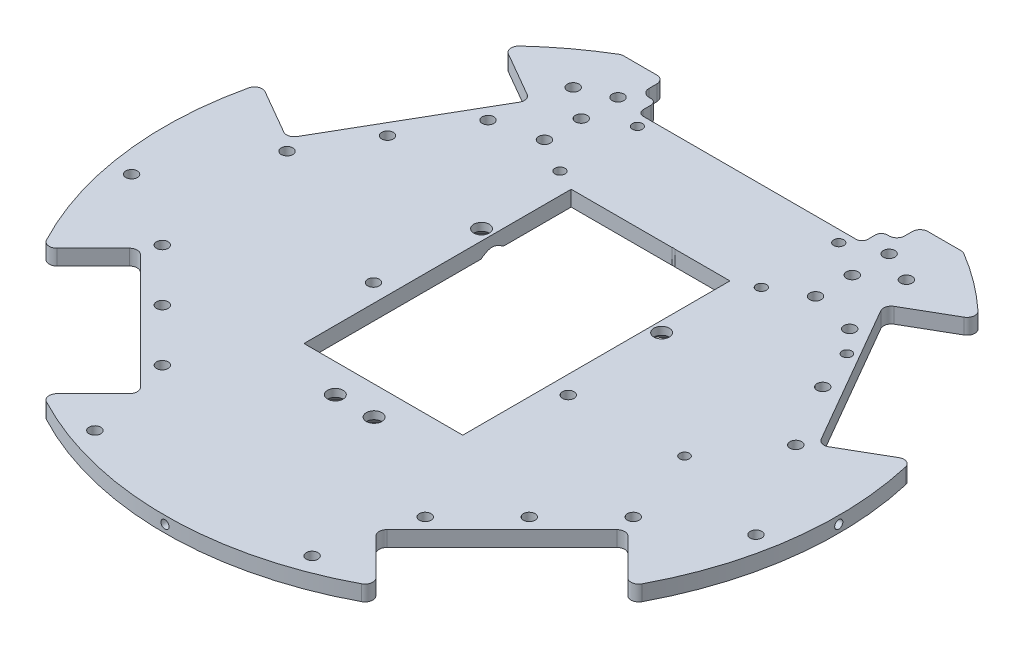
SolidWorks part; units mm, degrees
ref_plane "Front Plane" through (0, 0, 0) normal (0, 0, 1) x (1, 0, 0)
ref_plane "Top Plane" through (0, 0, 0) normal (0, 1, 0) x (1, 0, 0)
ref_plane "Right Plane" through (0, 0, 0) normal (1, 0, 0) x (0, 0, -1)
sketch "Sketch1" plane through (0, 0, 0) normal (0, 1, 0) x (1, 0, 0)
  line L0 (0, 75) -> (0, -70.0325) construction
  line L1 (0, 0) -> (57.1577, 33) construction
  line L2 (0, 0) -> (46.669, -46.669) construction
  line L3 (45.6577, 52.9186) -> (68.6577, 13.0814)
  line L4 (-44.0908, 75) -> (44.0908, 75) construction
  line L5 (62.9325, -30.4056) -> (30.4056, -62.9325)
  line L6 (45.6577, 52.9186) -> (61.1636, 61.8709)
  line L7 (68.6577, 13.0814) -> (84.1636, 22.0338)
  line L8 (30.4056, -62.9325) -> (43.0661, -75.593)
  line L9 (62.9325, -30.4056) -> (75.593, -43.0661)
  line L10 (-33, 69) -> (33, 69)
  line L11 (33, 69) -> (33, 75)
  line L12 (33, 75) -> (44.0908, 75)
  line L13 (0, 0) -> (-46.669, -46.669) construction
  line L14 (0, 0) -> (-57.1577, 33) construction
  line L15 (-33, 75) -> (-44.0908, 75)
  line L16 (-33, 69) -> (-33, 75)
  line L17 (-62.9325, -30.4056) -> (-75.593, -43.0661)
  line L18 (-30.4056, -62.9325) -> (-43.0661, -75.593)
  line L19 (-68.6577, 13.0814) -> (-84.1636, 22.0338)
  line L20 (-45.6577, 52.9186) -> (-61.1636, 61.8709)
  line L21 (-62.9325, -30.4056) -> (-30.4056, -62.9325)
  line L22 (-45.6577, 52.9186) -> (-68.6577, 13.0814)
  arc A0 (-43.0661, -75.593) -> (43.0661, -75.593) centre (0, 0) ccw
  arc A1 (61.1636, 61.8709) -> (44.0908, 75) centre (0, 0) ccw
  arc A2 (75.593, -43.0661) -> (84.1636, 22.0338) centre (0, 0) ccw
  arc A3 (-75.593, -43.0661) -> (-84.1636, 22.0338) centre (0, 0) cw
  arc A4 (-61.1636, 61.8709) -> (-44.0908, 75) centre (0, 0) cw
  point P27 (0, 69)
  dimension "D1" = 87
  dimension "D2" = 75
  dimension "D3" = 66
  dimension "D4" = 60
  dimension "D5" = 45
  dimension "D6" = 46
  dimension "D7" = 46
  dimension "D8" = 33
  dimension "D9" = 6
extrude "Boss-Extrude1" add sketch "Sketch1" along normal mid plane 4
fillet "Fillet1" radius 2 22 edges at (33, 0, -75) (-33, 0, -75) (44.0908, 0, -75) (68.6577, 0, -13.0814) (84.1636, 0, -22.0338) (45.6577, 0, -52.9186) (61.1636, 0, -61.8709) (62.9325, 0, 30.4056) (43.0661, 0, 75.593) (30.4056, 0, 62.9325) (75.593, 0, 43.0661) (-43.0661, 0, 75.593) (-30.4056, 0, 62.9325) (-75.593, 0, 43.0661) (-62.9325, 0, 30.4056) (-68.6577, 0, -13.0814) (-84.1636, 0, -22.0338) (-45.6577, 0, -52.9186) (33, 0, -69) (-33, 0, -69) (-44.0908, 0, -75) (-61.1636, 0, -61.8709)
sketch "Sketch2" plane through (0, -2, 0) normal (0, -1, 0) x (-1, 0, 0)
  line L0 (46.6936, 43.1244) -> (65.6936, 10.2154) construction
  line L1 (60.8112, -26.8701) -> (33.9411, -53.7401) construction
  line L2 (46.6577, 51.1865) -> (67.6577, 14.8135) construction
  line L3 (61.5183, -31.8198) -> (31.8198, -61.5183) construction
  line L4 (70.3897, 14.0814) -> (81.8562, 20.7016) construction
  line L5 (73.7091, -41.1822) -> (64.3467, -31.8198) construction
  line L6 (35, 65) -> (35, 46) construction
  line L7 (26, 61) -> (26, 41) construction
  line L8 (35, 75) -> (43.5431, 75) construction
  line L9 (-31, 69) -> (31, 69) construction
  line L10 (-31, 69) -> (31, 69) construction
  line L11 (0, 69) -> (0, -87) construction
  line L12 (-26, 61) -> (-26, 41) construction
  line L13 (-35, 65) -> (-35, 46) construction
  line L14 (-60.8112, -26.8701) -> (-33.9411, -53.7401) construction
  line L15 (-46.6936, 43.1244) -> (-65.6936, 10.2154) construction
  arc A0 (-40.7037, -76.8909) -> (40.7037, -76.8909) centre (0, 0) ccw construction
  point P0 (46.6936, 43.1244)
  point P1 (56.1936, 26.6699)
  point P2 (65.6936, 10.2154)
  point P3 (60.8112, -26.8701)
  point P4 (47.3762, -40.3051)
  point P5 (33.9411, -53.7401)
  point P18 (35, 65)
  point P19 (35, 55.5)
  point P20 (35, 46)
  point P21 (26, 61)
  point P22 (26, 41)
  point P29 (0, 69)
  point P34 (0, 69)
  point P48 (-35, 55.5)
  point P49 (-47.3762, -40.3051)
  point P50 (-56.1936, 26.6699)
  dimension "D1" = 38
  dimension "D2" = 38
  dimension "D3" = 4
  dimension "D4" = 4
  dimension "D5" = 18
  dimension "D6" = 18
  dimension "D7" = 19
  dimension "D8" = 35
  dimension "10" = 10
  dimension "D9" = 20
  dimension "D10" = 8
  dimension "D11" = 26
hole_wizard "CSK for M3 SFHCS1" positions "3DSketch1" profile "Sketch3" countersink size "M3" standard "ANSI Metric"
sketch3d "3DSketch1"
  point P0 (46.6936, -2, -43.1244)
  point P3 (56.1936, -2, -26.6699)
  point P6 (65.6936, -2, -10.2154)
  point P9 (60.8112, -2, 26.8701)
  point P12 (47.3762, -2, 40.3051)
  point P15 (33.9411, -2, 53.7401)
  point P18 (-33.9411, -2, 53.7401)
  point P21 (-47.3762, -2, 40.3051)
  point P24 (-60.8112, -2, 26.8701)
  point P27 (-46.6936, -2, -43.1244)
  point P30 (-56.1936, -2, -26.6699)
  point P33 (-65.6936, -2, -10.2154)
  point P36 (-35, -2, -65)
  point P39 (-35, -2, -55.5)
  point P42 (-35, -2, -46)
  point P45 (35, -2, -46)
  point P48 (35, -2, -55.5)
  point P51 (35, -2, -65)
sketch "Sketch3" plane through (46.6936, -2, -43.1244) normal (1, 0, 0) x (0, 0, -1)
  line L0 (0, 0) -> (0, 10.4013)
  line L1 (0, 10.4013) -> (1.5, 9.5)
  line L2 (1.5, 9.5) -> (1.5, 1.3)
  line L3 (1.5, 1.3) -> (2.8, 0)
  line L5 (2.8, 0) -> (0, 0)
  line L6 (-1.5, 1.3) -> (-2.8, 0) construction
  line L10 (0, 10.4013) -> (-1.5, 9.5) construction
  line L11 (0, -6.35) -> (0, 107.95) construction
  dimension "Hole Dia." = 3
  dimension "Hole Depth" = 9.5
  dimension "Near C'Sink Dia." = 5.6
  dimension "Near C'Sink Angle" = 90
  dimension "Drill Angle" = 118
sketch "Sketch4" plane through (0, -2, 0) normal (0, -1, 0) x (1, 0, 0)
  line L0 (0, 0) -> (-43.0182, -61.4364) construction
  line L1 (0, 0) -> (-28.0457, 77.0548) construction
  line L2 (0, -69) -> (0, 87) construction
  line L3 (0, 0) -> (-80.6164, 15) construction
  line L4 (0, -69) -> (0, 87) construction
  line L5 (0, 0) -> (80.6164, 15) construction
  line L6 (0, 0) -> (28.0457, 77.0548) construction
  line L7 (0, 0) -> (43.0182, -61.4364) construction
  dimension "D1" = 75
  dimension "D2" = 35
  dimension "D3" = 82
  dimension "D4" = 20
  dimension "D5" = 82
  dimension "D6" = 15
hole_wizard "CSK for M3 SFHCS2" positions "3DSketch2" profile "Sketch5" countersink size "M3" standard "ANSI Metric"
sketch3d "3DSketch2"
  point P0 (43.0182, -2, -61.4364)
  point P3 (80.6164, -2, 15)
  point P6 (28.0457, -2, 77.0548)
  point P9 (-28.0457, -2, 77.0548)
  point P12 (-80.6164, -2, 15)
  point P15 (-43.0182, -2, -61.4364)
sketch "Sketch5" plane through (43.0182, -2, -61.4364) normal (1, 0, 0) x (0, 0, -1)
  line L0 (0, 0) -> (0, 10.4013)
  line L1 (0, 10.4013) -> (1.5, 9.5)
  line L2 (1.5, 9.5) -> (1.5, 1.3)
  line L3 (1.5, 1.3) -> (2.8, 0)
  line L5 (2.8, 0) -> (0, 0)
  line L6 (-1.5, 1.3) -> (-2.8, 0) construction
  line L10 (0, 10.4013) -> (-1.5, 9.5) construction
  line L11 (0, -6.35) -> (0, 107.95) construction
  dimension "Hole Dia." = 3
  dimension "Hole Depth" = 9.5
  dimension "Near C'Sink Dia." = 5.6
  dimension "Near C'Sink Angle" = 90
  dimension "Drill Angle" = 118
hole_wizard "CSK for M3 SFHCS3" positions "3DSketch3" profile "Sketch6" countersink size "M3" standard "ANSI Metric"
sketch3d "3DSketch3"
  point P0 (26, -2, -41)
  point P3 (26, -2, -61)
  point P6 (-26, -2, -41)
  point P9 (-26, -2, -61)
sketch "Sketch6" plane through (26, -2, -41) normal (1, 0, 0) x (0, 0, -1)
  line L0 (0, 0) -> (0, 10.2811)
  line L1 (0, 10.2811) -> (1.3, 9.5)
  line L2 (1.3, 9.5) -> (1.3, 1)
  line L3 (1.3, 1) -> (2.3, 0)
  line L5 (2.3, 0) -> (0, 0)
  line L6 (-1.3, 1) -> (-2.3, 0) construction
  line L10 (0, 10.2811) -> (-1.3, 9.5) construction
  line L11 (0, -6.35) -> (0, 107.95) construction
  dimension "Hole Dia." = 2.6
  dimension "Hole Depth" = 9.5
  dimension "Near C'Sink Dia." = 4.6
  dimension "Near C'Sink Angle" = 90
  dimension "Drill Angle" = 118
sketch "Sketch7" plane through (0, 0, 0) normal (0, 1, 0) x (1, 0, 0)
  arc A0 (-84.8058, 19.4159) -> (-76.8909, -40.7037) centre (0, 0) ccw construction
  arc A1 (76.8909, -40.7037) -> (84.8058, 19.4159) centre (0, 0) ccw construction
  arc A2 (-40.7037, -76.8909) -> (40.7037, -76.8909) centre (0, 0) ccw construction
  arc A3 (59.2176, 63.736) -> (44.5676, 74.7176) centre (0, 0) ccw construction
  arc A4 (-44.5676, 74.7176) -> (-59.2176, 63.736) centre (0, 0) ccw construction
  point P0 (-86.2557, -11.3558)
  point P1 (86.2557, -11.3558)
  point P5 (0, -87)
  point P9 (52.1823, 69.6133)
  point P13 (-52.1823, 69.6133)
ref_plane "Plane1" through (87, 0, 0) normal (1, 0, 0) x (0, 0, -1)
sketch "Sketch9" plane through (87, 0, 0) normal (1, 0, 0) x (0, 0, -1)
  circle A0 centre (0, 0) radius 1.05
  dimension "D1" = 2.1
ref_plane "Plane2" through (0, 0, 87) normal (0, 0, 1) x (1, 0, 0)
sketch "Sketch10" plane through (0, 0, 87) normal (0, 0, 1) x (1, 0, 0)
  circle A0 centre (0, 0) radius 1.05
  dimension "D1" = 2.1
ref_plane "Plane3" through (52.1823, 0, -69.6133) normal (0.5998, 0, -0.8002) x (-0.8002, 0, -0.5998)
sketch "Sketch11" plane through (52.1823, 0, -69.6133) normal (0.5998, 0, -0.8002) x (-0.8002, 0, -0.5998)
  circle A0 centre (0, 0) radius 1.05
  dimension "D1" = 2.1
sketch "Sketch12" plane through (0, 2, 0) normal (0, 1, 0) x (1, 0, 0)
  line L0 (-23.25, 18) -> (23.25, 18) construction
  line L1 (25.15, -8) -> (-25.15, -8) construction
  line L2 (-5, -38) -> (5, -38) construction
  line L3 (31, 69) -> (-31, 69) construction
  line L4 (-35, 75) -> (-43.5431, 75) construction
  point P0 (-23.25, 18)
  point P1 (23.25, 18)
  point P2 (-5, -38)
  point P3 (5, -38)
  point P4 (-25.15, -8)
  point P5 (25.15, -8)
  point P14 (0, 18)
  point P16 (0, -8)
  point P17 (0, -38)
  dimension "D1" = 51
  dimension "D2" = 83
  dimension "D3" = 56
  dimension "D4" = 50.3
  dimension "D5" = 10
  dimension "D6" = 46.5
sketch "Sketch14" plane through (0, -2, 0) normal (0, -1, 0) x (1, 0, 0)
  point P0 (23.25, -18)
  point P1 (-23.25, -18)
  point P3 (-25.15, 8)
  point P5 (25.15, 8)
  point P7 (5, 38)
  point P9 (-5, 38)
hole_wizard "CSK for M4 SFHCS3" positions "3DSketch7" profile "Sketch16" countersink size "M4" standard "ANSI Metric"
sketch3d "3DSketch7"
  point P0 (23.25, -2, -18)
  point P3 (-23.25, -2, -18)
  point P6 (-5, -2, 38)
  point P9 (5, -2, 38)
sketch "Sketch16" plane through (23.25, -2, -18) normal (1, 0, 0) x (0, 0, -1)
  line L0 (0, 0) -> (0, 10.7017)
  line L1 (0, 10.7017) -> (2, 9.5)
  line L2 (2, 9.5) -> (2, 2)
  line L3 (2, 2) -> (4, 0)
  line L5 (4, 0) -> (0, 0)
  line L6 (-2, 2) -> (-4, 0) construction
  line L10 (0, 10.7017) -> (-2, 9.5) construction
  line L11 (0, -6.35) -> (0, 107.95) construction
  dimension "Hole Dia." = 4
  dimension "Hole Depth" = 9.5
  dimension "Near C'Sink Dia." = 8
  dimension "Near C'Sink Angle" = 90
  dimension "Drill Angle" = 118
hole_wizard "CSK for M3 SFHCS4" positions "3DSketch8" profile "Sketch17" countersink size "M3" standard "ANSI Metric"
sketch3d "3DSketch8"
  point P0 (25.15, -2, 8)
  point P3 (-25.15, -2, 8)
sketch "Sketch17" plane through (25.15, -2, 8) normal (1, 0, 0) x (0, 0, -1)
  line L0 (0, 0) -> (0, 10.4013)
  line L1 (0, 10.4013) -> (1.5, 9.5)
  line L2 (1.5, 9.5) -> (1.5, 1.3)
  line L3 (1.5, 1.3) -> (2.8, 0)
  line L5 (2.8, 0) -> (0, 0)
  line L6 (-1.5, 1.3) -> (-2.8, 0) construction
  line L10 (0, 10.4013) -> (-1.5, 9.5) construction
  line L11 (0, -6.35) -> (0, 107.95) construction
  dimension "Hole Dia." = 3
  dimension "Hole Depth" = 9.5
  dimension "Near C'Sink Dia." = 5.6
  dimension "Near C'Sink Angle" = 90
  dimension "Drill Angle" = 118
extrude "Cut-Extrude1" cut sketch "Sketch9" against normal blind 8
extrude "Cut-Extrude2" cut sketch "Sketch10" against normal blind 8
extrude "Cut-Extrude3" cut sketch "Sketch11" against normal blind 8
mirror "Mirror1" about plane through (0, 0, 0) normal (1, 0, 0) of "Cut-Extrude3", "Cut-Extrude2", "Cut-Extrude1"
sketch "Sketch18" plane through (0, 2, 0) normal (0, 1, 0) x (1, 0, 0)
  line L0 (-44.8999, 78) -> (44.8999, 78) construction
  line L1 (-35, 75) -> (-43.5431, 75) construction
  circle A0 centre (0, 0) radius 90 construction
  dimension "D1" = 180
  dimension "D2" = 3
hole_wizard "M2.5x0.45 Tapped Hole1" positions "3DSketch9" profile "Sketch19" tap size "M2.5x0.45" standard "ANSI Metric"
sketch3d "3DSketch9"
  line L0 (-35, 2, -75) -> (-43.5431, 2, -75) construction
  line L1 (43.5431, 2, -75) -> (35, 2, -75) construction
  line L2 (-35, -2, -75) -> (-43.5431, -2, -75) construction
  point P0 (-39.2715, 0, -75)
  point P2 (39.4456, 0, -75)
  point P11 (-39.2715, -2, -75)
  dimension "D1" = 2
  dimension "D2" = 2
sketch "Sketch19" plane through (-39.2715, 0, -75) normal (1, 0, 0) x (0, 1, 0)
  line L0 (0, 0) -> (0, 6.9659)
  line L1 (0, 6.9659) -> (1.025, 6.35)
  line L2 (1.025, 6.35) -> (1.025, 0)
  line L5 (1.025, 0) -> (0, 0)
  line L10 (0, 6.9659) -> (-1.025, 6.35) construction
  line L11 (0, -6.35) -> (0, 107.95) construction
  dimension "Tap Drill Dia." = 2.05
  dimension "Tap Drill Depth" = 6.35
  dimension "Drill Angle" = 118
sketch "Sketch21" plane through (0, 2, 0) normal (0, 1, 0) x (1, 0, 0)
  line L17 (43.5431, 75) -> (35, 75)
  line L18 (33, 73) -> (33, 71)
  line L19 (31, 69) -> (-31, 69)
  line L20 (-33, 71) -> (-33, 73)
  line L21 (-35, 75) -> (-43.5431, 75)
  line L22 (-58.8562, 60.5388) -> (-47.3897, 53.9186)
  line L23 (-46.6577, 51.1865) -> (-67.6577, 14.8135)
  line L24 (-70.3897, 14.0814) -> (-81.8562, 20.7016)
  line L25 (-73.7091, -41.1822) -> (-64.3467, -31.8198)
  line L26 (-61.5183, -31.8198) -> (-31.8198, -61.5183)
  line L27 (-31.8198, -64.3467) -> (-41.1822, -73.7091)
  line L28 (41.1822, -73.7091) -> (31.8198, -64.3467)
  line L29 (31.8198, -61.5183) -> (61.5183, -31.8198)
  line L30 (64.3467, -31.8198) -> (73.7091, -41.1822)
  line L31 (81.8562, 20.7016) -> (70.3897, 14.0814)
  line L32 (67.6577, 14.8135) -> (46.6577, 51.1865)
  line L33 (47.3897, 53.9186) -> (58.8562, 60.5388)
  line L34 (43.5431, 75) -> (35, 75)
  line L35 (33, 73) -> (33, 71)
  line L36 (31, 69) -> (-31, 69)
  line L37 (-33, 71) -> (-33, 73)
  line L38 (-35, 75) -> (-43.5431, 75)
  line L39 (-58.8562, 60.5388) -> (-47.3897, 53.9186)
  line L40 (-46.6577, 51.1865) -> (-67.6577, 14.8135)
  line L41 (-70.3897, 14.0814) -> (-81.8562, 20.7016)
  line L42 (-73.7091, -41.1822) -> (-64.3467, -31.8198)
  line L43 (-61.5183, -31.8198) -> (-31.8198, -61.5183)
  line L44 (-31.8198, -64.3467) -> (-41.1822, -73.7091)
  line L45 (41.1822, -73.7091) -> (31.8198, -64.3467)
  line L46 (31.8198, -61.5183) -> (61.5183, -31.8198)
  line L47 (64.3467, -31.8198) -> (73.7091, -41.1822)
  line L48 (81.8562, 20.7016) -> (70.3897, 14.0814)
  line L49 (67.6577, 14.8135) -> (46.6577, 51.1865)
  line L50 (47.3897, 53.9186) -> (58.8562, 60.5388)
  circle A1 centre (53.8103, -6.6373) radius 1.25
  circle A2 centre (53.8103, -6.6373) radius 1.25
  circle A3 centre (3.8103, -6.6373) radius 1.25
  circle A4 centre (3.8103, -6.6373) radius 1.25
  circle A5 centre (5.8853, 37.2127) radius 1.25
  circle A6 centre (5.8853, 37.2127) radius 1.25
  circle A7 centre (51.8853, 37.2127) radius 1.25
  circle A8 centre (51.8853, 37.2127) radius 1.25
  arc A27 (35, 75) -> (33, 73) centre (35, 73) ccw
  arc A28 (31, 69) -> (33, 71) centre (31, 71) ccw
  arc A29 (-33, 71) -> (-31, 69) centre (-31, 71) ccw
  arc A30 (-33, 73) -> (-35, 75) centre (-35, 73) ccw
  arc A31 (-43.5431, 75) -> (-44.5676, 74.7176) centre (-43.5431, 73) ccw
  arc A32 (-44.5676, 74.7176) -> (-59.2176, 63.736) centre (0, 0) ccw
  arc A33 (-59.2176, 63.736) -> (-58.8562, 60.5388) centre (-57.8562, 62.2708) ccw
  arc A34 (-46.6577, 51.1865) -> (-47.3897, 53.9186) centre (-48.3897, 52.1865) ccw
  arc A35 (-70.3897, 14.0814) -> (-67.6577, 14.8135) centre (-69.3897, 15.8135) ccw
  arc A36 (-81.8562, 20.7016) -> (-84.8058, 19.4159) centre (-82.8562, 18.9696) ccw
  arc A37 (-84.8058, 19.4159) -> (-76.8909, -40.7037) centre (0, 0) ccw
  arc A38 (-76.8909, -40.7037) -> (-73.7091, -41.1822) centre (-75.1233, -39.768) ccw
  arc A39 (-61.5183, -31.8198) -> (-64.3467, -31.8198) centre (-62.9325, -33.234) ccw
  arc A40 (-31.8198, -64.3467) -> (-31.8198, -61.5183) centre (-33.234, -62.9325) ccw
  arc A41 (-41.1822, -73.7091) -> (-40.7037, -76.8909) centre (-39.768, -75.1233) ccw
  arc A42 (-40.7037, -76.8909) -> (40.7037, -76.8909) centre (0, 0) ccw
  arc A43 (40.7037, -76.8909) -> (41.1822, -73.7091) centre (39.768, -75.1233) ccw
  arc A44 (31.8198, -61.5183) -> (31.8198, -64.3467) centre (33.234, -62.9325) ccw
  arc A45 (64.3467, -31.8198) -> (61.5183, -31.8198) centre (62.9325, -33.234) ccw
  arc A46 (73.7091, -41.1822) -> (76.8909, -40.7037) centre (75.1233, -39.768) ccw
  arc A47 (76.8909, -40.7037) -> (84.8058, 19.4159) centre (0, 0) ccw
  arc A48 (84.8058, 19.4159) -> (81.8562, 20.7016) centre (82.8562, 18.9696) ccw
  arc A49 (67.6577, 14.8135) -> (70.3897, 14.0814) centre (69.3897, 15.8135) ccw
  arc A50 (47.3897, 53.9186) -> (46.6577, 51.1865) centre (48.3897, 52.1865) ccw
  arc A51 (58.8562, 60.5388) -> (59.2176, 63.736) centre (57.8562, 62.2708) ccw
  arc A52 (59.2176, 63.736) -> (44.5676, 74.7176) centre (0, 0) ccw
  arc A53 (44.5676, 74.7176) -> (43.5431, 75) centre (43.5431, 73) ccw
  arc A54 (35, 75) -> (33, 73) centre (35, 73) ccw
  arc A55 (31, 69) -> (33, 71) centre (31, 71) ccw
  arc A56 (-33, 71) -> (-31, 69) centre (-31, 71) ccw
  arc A57 (-33, 73) -> (-35, 75) centre (-35, 73) ccw
  arc A58 (-43.5431, 75) -> (-44.5676, 74.7176) centre (-43.5431, 73) ccw
  arc A59 (-44.5676, 74.7176) -> (-59.2176, 63.736) centre (0, 0) ccw
  arc A60 (-59.2176, 63.736) -> (-58.8562, 60.5388) centre (-57.8562, 62.2708) ccw
  arc A61 (-46.6577, 51.1865) -> (-47.3897, 53.9186) centre (-48.3897, 52.1865) ccw
  arc A62 (-70.3897, 14.0814) -> (-67.6577, 14.8135) centre (-69.3897, 15.8135) ccw
  arc A63 (-81.8562, 20.7016) -> (-84.8058, 19.4159) centre (-82.8562, 18.9696) ccw
  arc A64 (-84.8058, 19.4159) -> (-76.8909, -40.7037) centre (0, 0) ccw
  arc A65 (-76.8909, -40.7037) -> (-73.7091, -41.1822) centre (-75.1233, -39.768) ccw
  arc A66 (-61.5183, -31.8198) -> (-64.3467, -31.8198) centre (-62.9325, -33.234) ccw
  arc A67 (-31.8198, -64.3467) -> (-31.8198, -61.5183) centre (-33.234, -62.9325) ccw
  arc A68 (-41.1822, -73.7091) -> (-40.7037, -76.8909) centre (-39.768, -75.1233) ccw
  arc A69 (-40.7037, -76.8909) -> (40.7037, -76.8909) centre (0, 0) ccw
  arc A70 (40.7037, -76.8909) -> (41.1822, -73.7091) centre (39.768, -75.1233) ccw
  arc A71 (31.8198, -61.5183) -> (31.8198, -64.3467) centre (33.234, -62.9325) ccw
  arc A72 (64.3467, -31.8198) -> (61.5183, -31.8198) centre (62.9325, -33.234) ccw
  arc A73 (73.7091, -41.1822) -> (76.8909, -40.7037) centre (75.1233, -39.768) ccw
  arc A74 (76.8909, -40.7037) -> (84.8058, 19.4159) centre (0, 0) ccw
  arc A75 (84.8058, 19.4159) -> (81.8562, 20.7016) centre (82.8562, 18.9696) ccw
  arc A76 (67.6577, 14.8135) -> (70.3897, 14.0814) centre (69.3897, 15.8135) ccw
  arc A77 (47.3897, 53.9186) -> (46.6577, 51.1865) centre (48.3897, 52.1865) ccw
  arc A78 (58.8562, 60.5388) -> (59.2176, 63.736) centre (57.8562, 62.2708) ccw
  arc A79 (59.2176, 63.736) -> (44.5676, 74.7176) centre (0, 0) ccw
  arc A80 (44.5676, 74.7176) -> (43.5431, 75) centre (43.5431, 73) ccw
  dimension "D1" = 0
  dimension "D2" = 0
  dimension "D3" = 0
  dimension "D4" = 0
  dimension "D5" = 0
extrude "Cut-Extrude4" cut sketch "Sketch21" against normal up to next contours A2 | A8 | A4 | A6
ref_plane "Plane4" through (-31, 2, -69) normal (-1, 0, 0) x (0, 0, 1)
ref_plane "Plane5" through (-31, 2, -69) normal (-1, 0, 0) x (0, 0, 1)
ref_plane "Plane6" through (0, 0, -69) normal (0, 0, -1) x (-1, 0, 0)
sketch "Sketch24" plane through (0, 0, -69) normal (0, 0, -1) x (-1, 0, 0)
  line L0 (-33, -2) -> (-33, 2) construction
  line L1 (-29, 2) -> (29, 2)
  line L2 (-29, 2) -> (-29, -2)
  line L3 (-29, -2) -> (29, -2)
  line L4 (29, 2) -> (29, -2)
  line L5 (33, 2) -> (33, -2) construction
  line L6 (-31, 2) -> (31, 2) construction
  line L7 (-31, -2) -> (31, -2) construction
  dimension "D1" = 4
  dimension "D2" = 4
extrude "Cut-Extrude5" cut sketch "Sketch24" against normal blind 5
fillet "Fillet2" radius 1.5 4 edges at (-29, 0, -69) (-29, 0, -64) (29, 0, -64) (29, 0, -69)
sketch "Sketch25" plane through (0, 2, 0) normal (0, 1, 0) x (1, 0, 0)
  line L0 (3, -38) -> (-3, -38) construction
  circle A0 centre (5, -38) radius 2 construction
  circle A1 centre (-5, -38) radius 2 construction
  point P7 (0, -38)
ref_plane "Plane7" through (0, 2, 38) normal (-1, 0, 0) x (0, 0, 1)
sketch "Sketch26" plane through (0, 2, 0) normal (0, 1, 0) x (1, 0, 0)
  line L0 (20.5, 38.4) -> (-20.5, 38.4)
  line L1 (-20.5, 38.4) -> (-20.5, -30.6)
  line L2 (-20.5, -30.6) -> (20.5, -30.6)
  line L3 (20.5, -30.6) -> (20.5, 38.4)
  line L4 (-27.5, 64) -> (27.5, 64) construction
  dimension "D1" = 25.6
  dimension "D2" = 69
  dimension "D3" = 20.5
  dimension "D4" = 20.5
extrude "Cut-Extrude6" cut sketch "Sketch26" against normal up to surface (4 mm away)
